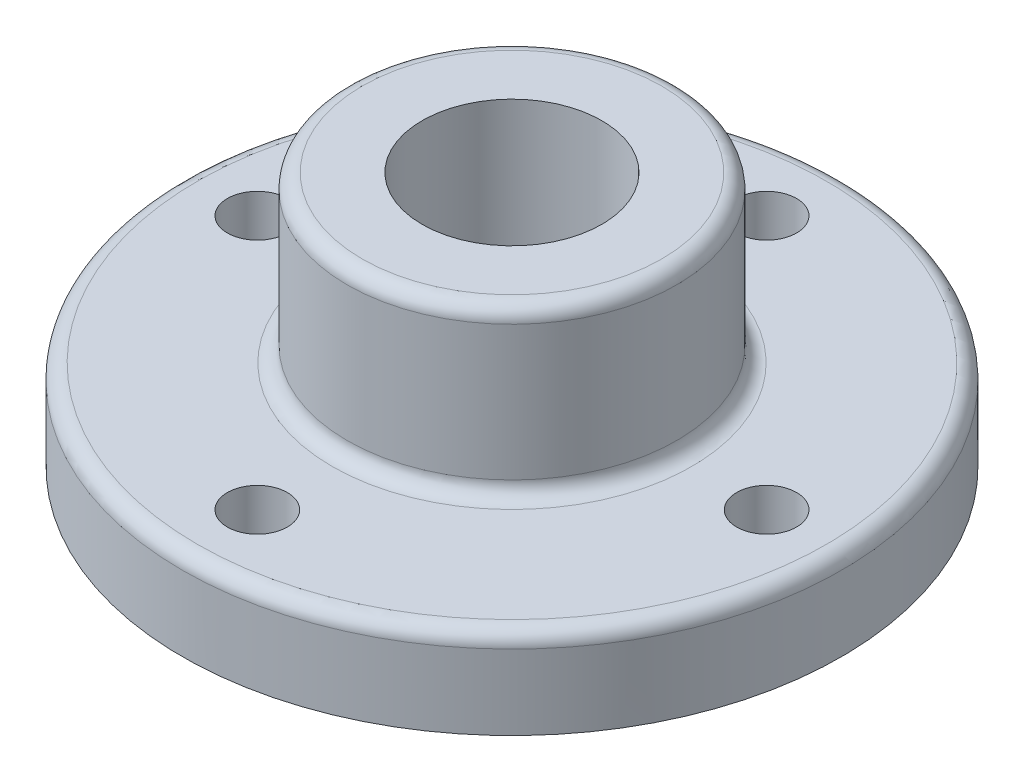
SolidWorks part; units mm, degrees
material "6063-T6"
ref_plane "Plan de face" through (0, 0, 0) normal (0, 0, 1) x (1, 0, 0)
ref_plane "Plan de dessus" through (0, 0, 0) normal (0, 1, 0) x (1, 0, 0)
ref_plane "Plan de droite" through (0, 0, 0) normal (1, 0, 0) x (0, 0, -1)
sketch "Esquisse1" plane through (0, 0, 0) normal (0, 1, 0) x (1, 0, 0)
  circle A0 centre (0, 0) radius 69.85
  dimension "D1" = 139.7
extrude "Base" add sketch "Esquisse1" along normal blind 19.05
sketch "Esquisse2" plane through (0, 19.05, 0) normal (0, 1, 0) x (1, 0, 0)
  circle A0 centre (0, 0) radius 34.925
  dimension "D1" = 69.85
extrude "Deuxieme base" add sketch "Esquisse2" along normal blind 34.925
fillet "Arrondi" radius 3.175 3 edges at (0, 19.05, 34.925) (0, 19.05, 69.85) (0, 53.975, 34.925)
sketch "Esquisse3" plane through (0, 53.975, 0) normal (0, 1, 0) x (1, 0, 0)
  circle A0 centre (0, 0) radius 19.05
  dimension "D1" = 38.1
extrude "Enlèv. mat.-Extru.1" cut sketch "Esquisse3" against normal blind 76.2
sketch "Esquisse4" plane through (0, 19.05, 0) normal (0, 1, 0) x (1, 0, 0)
  circle A1 centre (53.975, 0) radius 6.35
  circle A2 centre (0, 53.975) radius 6.35
  circle A3 centre (-53.975, 0) radius 6.35
  circle A4 centre (0, -53.975) radius 6.35
extrude "Enlèv. mat.-Extru.2" cut sketch "Esquisse4" against normal blind 76.2
